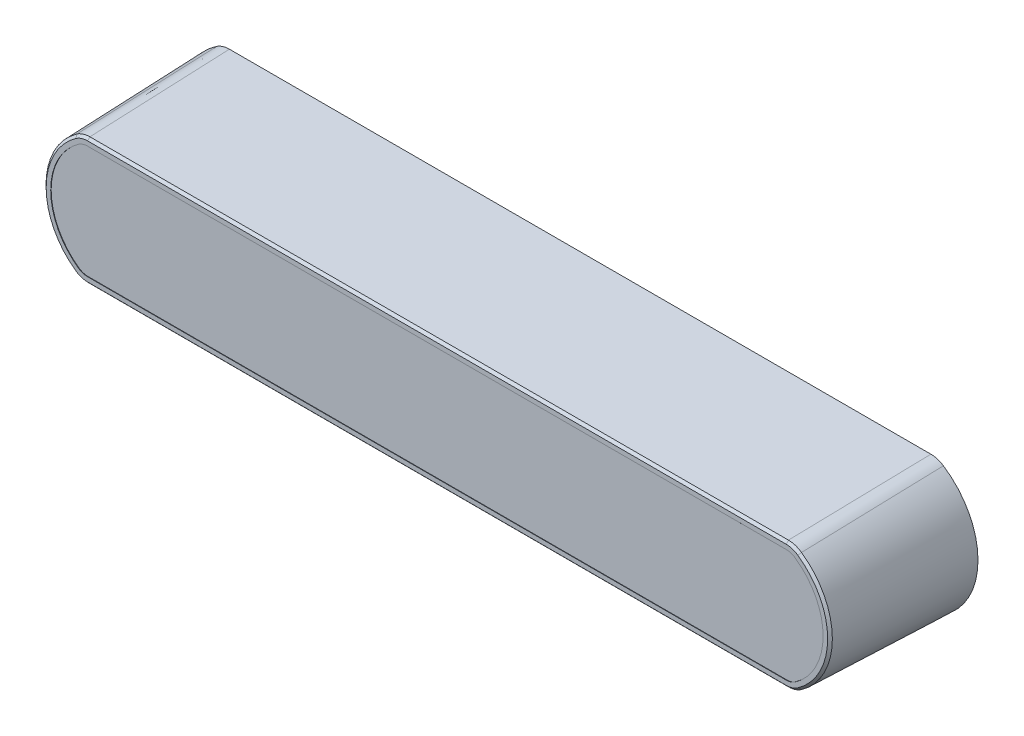
SolidWorks part; units mm, degrees
ref_plane "Front Plane" through (0, 0, 0) normal (0, 0, 1) x (1, 0, 0)
ref_plane "Top Plane" through (0, 0, 0) normal (0, 1, 0) x (1, 0, 0)
ref_plane "Right Plane" through (0, 0, 0) normal (1, 0, 0) x (0, 0, -1)
sketch "Sketch1" plane through (0, 0, 0) normal (0, 0, 1) x (1, 0, 0)
  line L0 (87.5, 0) -> (-87.5, 0) construction
  line L5 (78.5, 15) -> (78.5, -15) construction
  line L6 (0, 15) -> (0, -15) construction
  line L7 (-78.5, 15) -> (78.5, 15)
  line L8 (-78.5, -15) -> (78.5, -15)
  arc A2 (78.5, 15) -> (78.5, -15) centre (70.5, 0) cw
  arc A3 (-78.5, 15) -> (-78.5, -15) centre (-70.5, 0) ccw
  point P3 (0, 0)
  point P7 (78.5, 0)
  point P9 (0, 0)
  point P10 (87.5, 0)
  point P14 (0, 15)
  dimension "D3" = 30
  dimension "D2" = 17
  dimension "D1" = 175
extrude "Boss-Extrude1" add sketch "Sketch1" along normal blind 31.5 draft 1.9
fillet "Fillet1" radius 5 4 edges
chamfer "Chamfer2" distance 0.5 angle 45 8 edges at (86.455, 0, 31.5) (78.1749, 13.7654, 31.5) (78.4653, -13.6733, 31.5) (0, 13.955, 31.5) (0, -13.955, 31.5) (-78.2145, 13.754, 31.5) (-78.4315, -13.6851, 31.5) (-86.455, 0, 31.5)
sketch "Sketch2" plane through (0, 0, 0) normal (0, 0, -1) x (1, 0, 0)
  line L0 (0, -15) -> (0, 15) construction
  line L1 (77.1341, -15) -> (-77.1341, -15) construction
  line L2 (-77.1341, 15) -> (77.1341, 15) construction
  circle A0 centre (0, 9) radius 2
  dimension "D1" = 4
  dimension "D2" = 6
extrude "Boss-Extrude2" add sketch "Sketch2" along normal blind 10
sketch "Sketch3" plane through (0, 0, 31.5) normal (0, 0, 1) x (1, 0, 0)
  line L4 (-76.8164, -12.4376) -> (76.8163, -12.4376)
  line L5 (76.8164, 12.4376) -> (-76.8163, 12.4376)
  line L6 (-76.8164, -12.4376) -> (76.8163, -12.4376)
  line L7 (76.8164, 12.4376) -> (-76.8163, 12.4376)
  arc A4 (78.8098, -11.8064) -> (78.8098, 11.8064) centre (70.5, 0) ccw
  arc A5 (-78.8098, 11.8064) -> (-78.8098, -11.8064) centre (-70.5, 0) ccw
  arc A6 (78.8098, -11.8064) -> (78.8098, 11.8064) centre (70.5, 0) ccw
  arc A7 (-78.8098, 11.8064) -> (-78.8098, -11.8064) centre (-70.5, 0) ccw
  spline S8 degree 3 poles (-383.3297, 2951.3553) (-37.6026, 403.9092) (46.1129, -17.2088) (77.5187, -12.3703) (77.6923, -12.3297) (98.0889, -5.8805) (57.2048, 186.9196) (-2824.8908, -741.3401) knots -44.532648 -44.532648 -44.532648 -44.532648 0.25 0.25 0.5 0.5 30.461711 30.461711 30.461711 30.461711 only from (76.8163, -12.4376) to (78.8098, -11.8064)
  spline S9 degree 3 poles (-1250.7538, -2676.7001) (-67.2572, -394.5195) (106.6639, -1.9637) (78.1967, 12.1556) (78.0314, 12.2223) (57.64, 18.6879) (-19.8954, -162.5071) (2871.2311, -1062.2451) knots -44.532648 -44.532648 -44.532648 -44.532648 0.25 0.25 0.5 0.5 30.461711 30.461711 30.461711 30.461711 only from (78.8098, 11.8064) to (76.8164, 12.4376)
  spline S10 degree 3 poles (1250.7537, 2676.7001) (67.2572, 394.5195) (-106.6639, 1.9637) (-78.1967, -12.1556) (-78.0314, -12.2223) (-57.64, -18.6879) (19.8954, 162.5071) (-2871.2311, 1062.2451) knots -44.532648 -44.532648 -44.532648 -44.532648 0.25 0.25 0.5 0.5 30.461711 30.461711 30.461711 30.461711 only from (-78.8098, -11.8064) to (-76.8164, -12.4376)
  spline S11 degree 3 poles (383.3297, -2951.3553) (37.6026, -403.9092) (-46.1129, 17.2088) (-77.5187, 12.3703) (-77.6923, 12.3297) (-98.0889, 5.8805) (-57.2048, -186.9196) (2824.8908, 741.3401) knots -44.532648 -44.532648 -44.532648 -44.532648 0.25 0.25 0.5 0.5 30.461711 30.461711 30.461711 30.461711 only from (-76.8163, 12.4376) to (-78.8098, 11.8064)
  spline S12 degree 3 poles (76.8163, -12.4376) (76.994, -12.4376) (77.17, -12.424) (77.5187, -12.3703) (77.6923, -12.3297) (78.1986, -12.1696) (78.5192, -12.0109) (78.8098, -11.8064) knots 0 0 0 0 0.25 0.25 0.5 0.5 1 1 1 1
  spline S13 degree 3 poles (78.8098, 11.8064) (78.6645, 11.9086) (78.5128, 11.9988) (78.1967, 12.1556) (78.0314, 12.2223) (77.5252, 12.3828) (77.1718, 12.4376) (76.8164, 12.4376) knots 0 0 0 0 0.25 0.25 0.5 0.5 1 1 1 1
  spline S14 degree 3 poles (-78.8098, -11.8064) (-78.6645, -11.9086) (-78.5128, -11.9988) (-78.1967, -12.1556) (-78.0314, -12.2223) (-77.5252, -12.3828) (-77.1718, -12.4376) (-76.8164, -12.4376) knots 0 0 0 0 0.25 0.25 0.5 0.5 1 1 1 1
  spline S15 degree 3 poles (-76.8163, 12.4376) (-76.994, 12.4376) (-77.17, 12.424) (-77.5187, 12.3703) (-77.6923, 12.3297) (-78.1986, 12.1696) (-78.5192, 12.0109) (-78.8098, 11.8064) knots 0 0 0 0 0.25 0.25 0.5 0.5 1 1 1 1
  dimension "D1" = 1
sketch "Sketch4" plane through (0, 0, 0) normal (0, 0, -1) x (1, 0, 0)
  line L14 (77.1341, 14) -> (-77.1341, 14)
  line L15 (-77.1341, -14) -> (77.1341, -14)
  line L16 (77.1341, 14) -> (-77.1341, 14)
  line L17 (-77.1341, -14) -> (77.1341, -14)
  arc A30 (-79.3434, -13.3339) -> (-77.1341, -14) centre (-77.1341, -10.0029) ccw
  arc A31 (-79.3434, 13.3339) -> (-79.3434, -13.3339) centre (-70.5, 0) ccw
  arc A32 (-77.1341, 14) -> (-79.3434, 13.3339) centre (-77.1341, 10.0029) ccw
  arc A33 (79.3434, 13.3339) -> (77.1341, 14) centre (77.1341, 10.0029) ccw
  arc A34 (79.3434, -13.3339) -> (79.3434, 13.3339) centre (70.5, 0) ccw
  arc A35 (77.1341, -14) -> (79.3434, -13.3339) centre (77.1341, -10.0029) ccw
  arc A36 (-79.3434, -13.3339) -> (-77.1341, -14) centre (-77.1341, -10.0029) ccw
  arc A37 (-79.3434, 13.3339) -> (-79.3434, -13.3339) centre (-70.5, 0) ccw
  arc A38 (-77.1341, 14) -> (-79.3434, 13.3339) centre (-77.1341, 10.0029) ccw
  arc A39 (79.3434, 13.3339) -> (77.1341, 14) centre (77.1341, 10.0029) ccw
  arc A40 (79.3434, -13.3339) -> (79.3434, 13.3339) centre (70.5, 0) ccw
  arc A41 (77.1341, -14) -> (79.3434, -13.3339) centre (77.1341, -10.0029) ccw
  dimension "D1" = 1
extrude "Cut-Extrude2" cut sketch "Sketch4" against normal blind 0.1
ref_plane "Plane1" through (0, -15, 0) normal (0, 1, 0) x (1, 0, 0)
sketch "Sketch5" plane through (0, -15, 0) normal (0, 1, 0) x (1, 0, 0)
  line L1 (0, -31.5) -> (0, 0) construction
  line L3 (-77.1341, 0) -> (77.1341, 0) construction
  line L5 (-76.8164, -31.5) -> (76.8164, -31.5) construction
  circle A0 centre (0, -16.8) radius 2.5
  dimension "D1" = 16.8
  dimension "D2" = 5
extrude "Cut-Extrude3" cut sketch "Sketch3" against normal blind 0.1
extrude "Cut-Extrude4" cut sketch "Sketch5" along normal blind 10 contours A0
